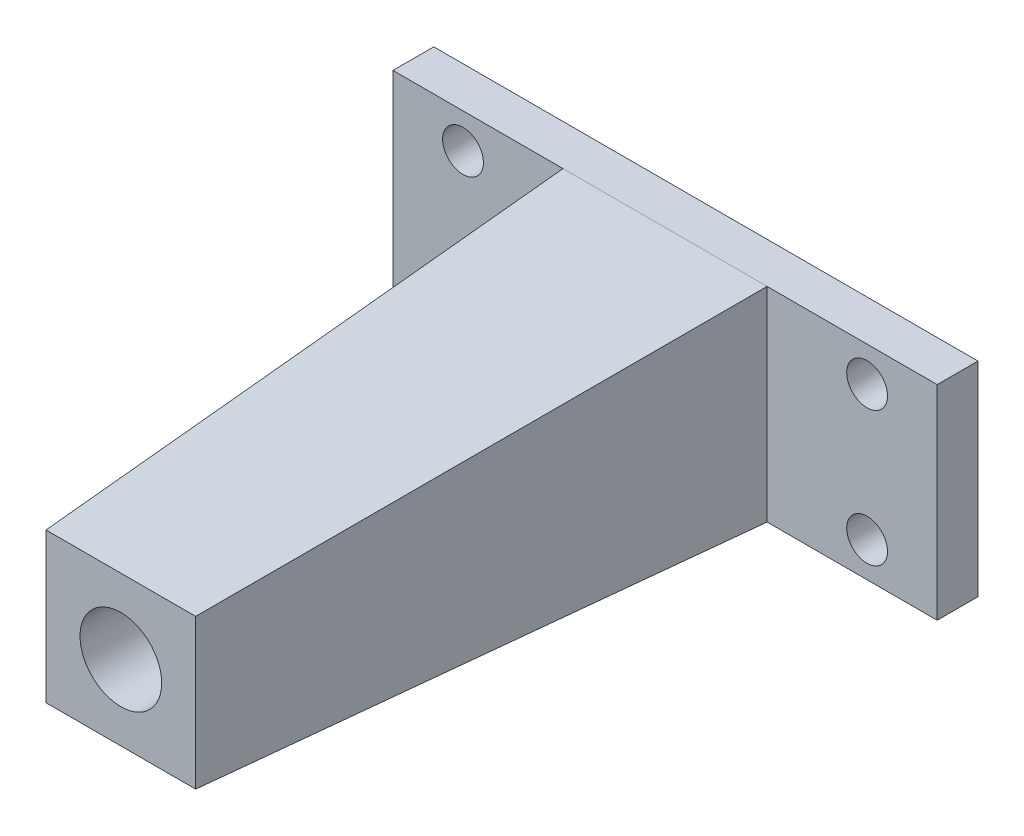
SolidWorks part; units mm, degrees
ref_plane "前视基准面" through (0, 0, 0) normal (0, 0, 1) x (1, 0, 0)
ref_plane "上视基准面" through (0, 0, 0) normal (0, 1, 0) x (1, 0, 0)
ref_plane "右视基准面" through (0, 0, 0) normal (1, 0, 0) x (0, 0, -1)
other "Configuration Table"
sketch "草图1" plane through (0, 0, 0) normal (0, 0, 1) x (1, 0, 0)
  line L1 (-20, -7.5) -> (20, -7.5)
  line L2 (-20, -7.5) -> (-20, 7.5)
  line L3 (-20, 7.5) -> (20, 7.5)
  line L4 (20, -7.5) -> (20, 7.5)
  line L5 (-20, -7.5) -> (20, 7.5) construction
  line L6 (-20, 7.5) -> (20, -7.5) construction
  line L7 (-4.95, -4.95) -> (4.95, -4.95) construction
  line L8 (-4.95, -4.95) -> (-4.95, 4.95) construction
  line L9 (-4.95, 4.95) -> (4.95, 4.95) construction
  line L10 (4.95, -4.95) -> (4.95, 4.95) construction
  line L11 (-4.95, -4.95) -> (4.95, 4.95) construction
  line L12 (-4.95, 4.95) -> (4.95, -4.95) construction
  circle A0 centre (0, 0) radius 3 construction
  circle A1 centre (4.95, 4.95) radius 1.5
  circle A2 centre (4.95, -4.95) radius 1.5
  circle A3 centre (-4.95, -4.95) radius 1.5
  circle A4 centre (-4.95, 4.95) radius 1.5
  dimension "D1" = 6
  dimension "D6" = 3
  dimension "D7" = 3
  dimension "D8" = 3
  dimension "D9" = 3
  dimension "D2" = 40
  dimension "D3" = 15
  dimension "D4" = 9.9
  dimension "D5" = 9.9
extrude "凸台-拉伸1" add sketch "草图1" along normal blind 3
sketch "草图2" plane through (0, 0, 3) normal (0, 0, 1) x (1, 0, 0)
  line L1 (-7.5, -7.5) -> (7.5, -7.5)
  line L2 (-7.5, -7.5) -> (-7.5, 7.5)
  line L3 (-7.5, 7.5) -> (7.5, 7.5)
  line L4 (7.5, -7.5) -> (7.5, 7.5)
  line L5 (-7.5, -7.5) -> (7.5, 7.5) construction
  line L6 (-7.5, 7.5) -> (7.5, -7.5) construction
  point P0 (0, 0)
  dimension "D1" = 15
  dimension "D2" = 15
ref_plane "基准面1" through (0, 0, 43) normal (0, 0, 1) x (1, 0, 0)
sketch "草图3" plane through (0, 0, 43) normal (0, 0, 1) x (1, 0, 0)
  line L8 (-5.5, -5.5) -> (5.5, -5.5)
  line L9 (5.5, -5.5) -> (5.5, 5.5)
  line L10 (5.5, 5.5) -> (-5.5, 5.5)
  line L11 (-5.5, 5.5) -> (-5.5, -5.5)
  line L12 (-5.5, -5.5) -> (5.5, -5.5)
  line L13 (5.5, -5.5) -> (5.5, 5.5)
  line L14 (5.5, 5.5) -> (-5.5, 5.5)
  line L15 (-5.5, 5.5) -> (-5.5, -5.5)
  dimension "D1" = 2
loft "放样1" add profiles "草图3", "草图2"
sketch "草图5" plane through (0, 0, 0) normal (0, 0, -1) x (-1, 0, 0)
  circle A0 centre (4.95, -4.95) radius 1.5 construction
  circle A1 centre (4.95, -4.95) radius 1.5
  circle A2 centre (4.95, 4.95) radius 1.5 construction
  circle A3 centre (-4.95, 4.95) radius 1.5 construction
  circle A4 centre (-4.95, -4.95) radius 1.5 construction
  circle A5 centre (4.95, 4.95) radius 1.5
  circle A6 centre (-4.95, 4.95) radius 1.5
  circle A7 centre (-4.95, -4.95) radius 1.5
extrude "切除-拉伸3" cut sketch "草图5" against normal blind 8
sketch "草图6" plane through (0, 0, 43) normal (0, 0, 1) x (1, 0, 0)
  line L8 (-7.5, 7.5) -> (-7.5, -7.5)
  line L9 (-7.5, -7.5) -> (7.5, -7.5)
  line L10 (7.5, -7.5) -> (7.5, 7.5)
  line L11 (7.5, 7.5) -> (-7.5, 7.5)
  line L12 (-7.5, 7.5) -> (-7.5, -7.5)
  line L13 (-7.5, -7.5) -> (7.5, -7.5)
  line L14 (7.5, -7.5) -> (7.5, 7.5)
  line L15 (7.5, 7.5) -> (-7.5, 7.5)
  dimension "D1" = 2
sketch "草图8" plane through (0, 0, 43) normal (0, 0, 1) x (1, 0, 0)
  circle A0 centre (0, 0) radius 2.9996
  dimension "D1" = 5.9993
extrude "切除-拉伸4" cut sketch "草图8" against normal blind 15
sketch "草图9" plane through (0, 0, 0) normal (0, 0, -1) x (-1, 0, 0)
  circle A0 centre (-14.849, -4.95) radius 1.5 construction
  circle A1 centre (-14.849, -4.95) radius 1.5
  circle A2 centre (-14.849, 4.9495) radius 1.5 construction
  circle A3 centre (-14.849, 4.9495) radius 1.5
  circle A4 centre (14.8495, 4.9495) radius 1.5 construction
  circle A5 centre (14.8495, 4.9495) radius 1.5
  circle A6 centre (14.8495, -4.95) radius 1.5 construction
  circle A7 centre (14.8495, -4.95) radius 1.5
extrude "切除-拉伸5" cut sketch "草图9" against normal blind 15
